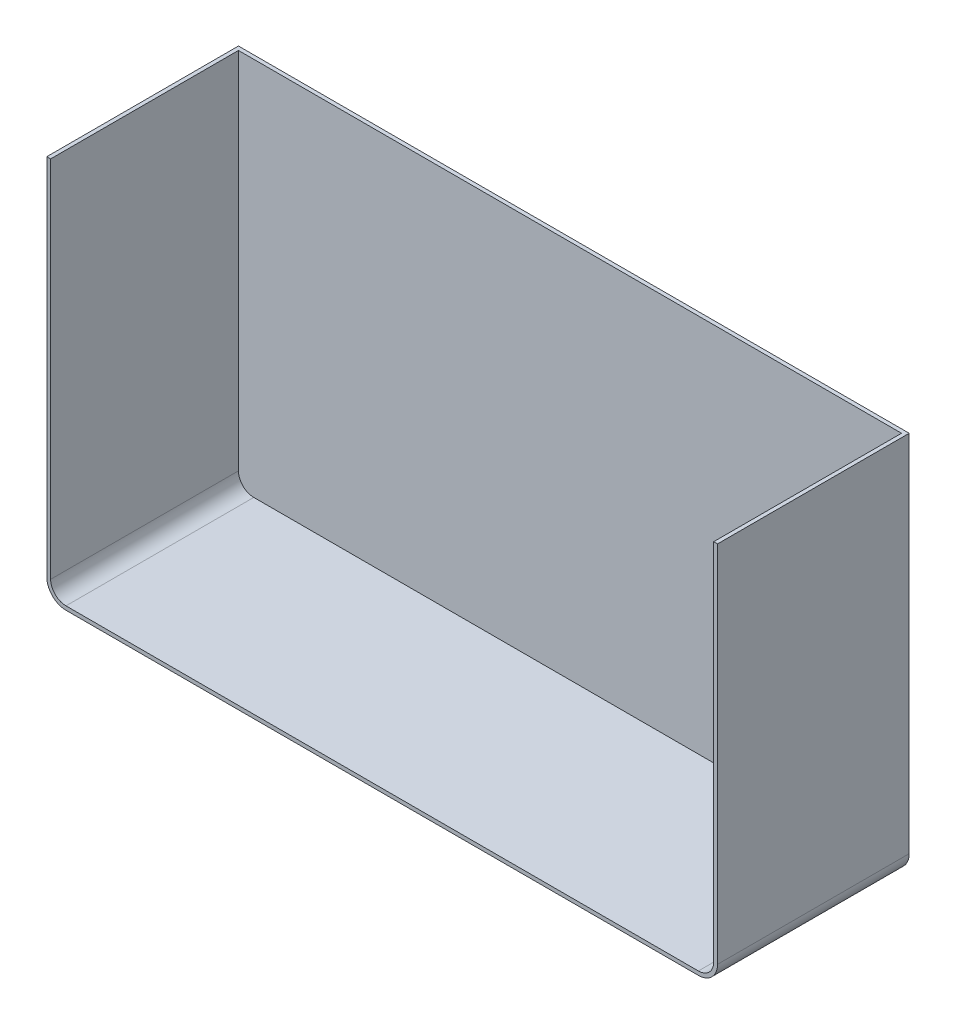
SolidWorks part; units mm, degrees
ref_plane "前视基准面" through (0, 0, 0) normal (0, 0, 1) x (1, 0, 0)
ref_plane "上视基准面" through (0, 0, 0) normal (0, 1, 0) x (1, 0, 0)
ref_plane "右视基准面" through (0, 0, 0) normal (1, 0, 0) x (0, 0, -1)
other "Configuration Table"
sketch "草图1" plane through (0, 0, 0) normal (0, 0, 1) x (1, 0, 0)
  line L1 (-175, -100) -> (175, -100)
  line L2 (-175, -100) -> (-175, 100)
  line L3 (-175, 100) -> (175, 100)
  line L4 (175, -100) -> (175, 100)
  line L5 (-175, -100) -> (175, 100) construction
  line L6 (-175, 100) -> (175, -100) construction
  point P0 (0, 0)
  dimension "D1" = 350
  dimension "D2" = 200
extrude "凸台-拉伸1" add sketch "草图1" along normal blind 100
fillet "圆角1" radius 10 2 edges at (175, -100, 50) (-175, -100, 50)
shell "抽壳1" thickness 2
